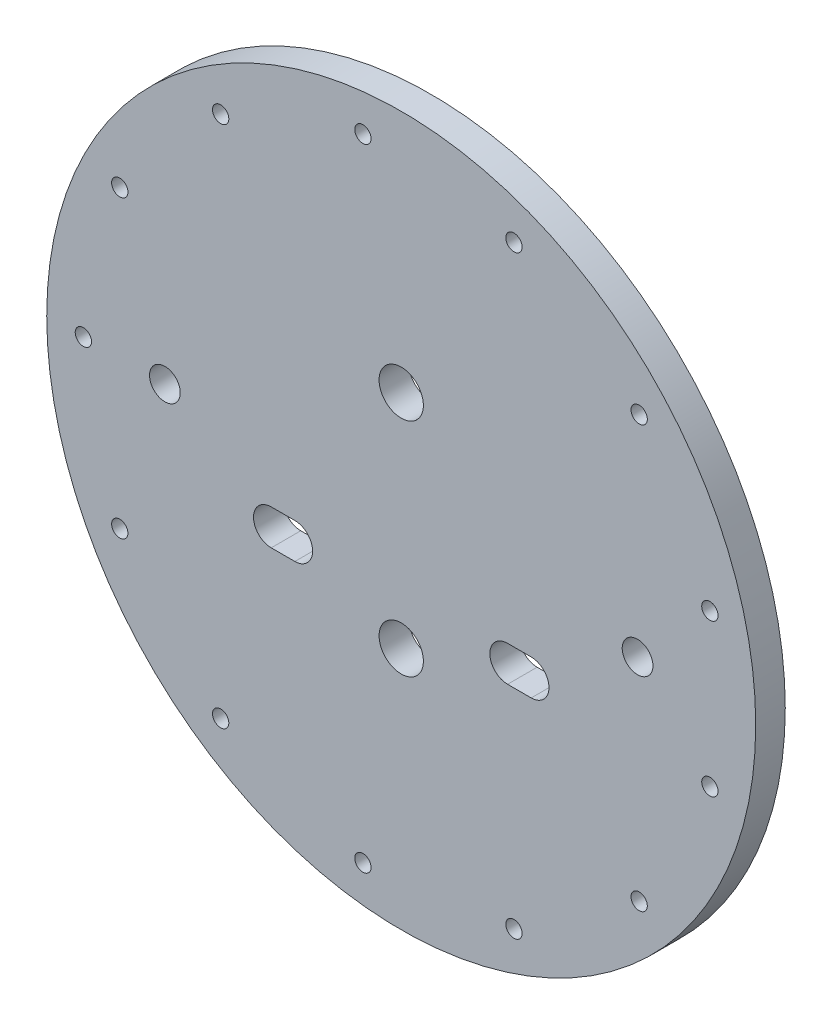
SolidWorks part; units mm, degrees
material "Balsa"
ref_plane "Front" through (0, 0, 0) normal (0, 0, 1) x (1, 0, 0)
ref_plane "Top" through (0, 0, 0) normal (0, 1, 0) x (1, 0, 0)
ref_plane "Right" through (0, 0, 0) normal (1, 0, 0) x (0, 0, -1)
sketch "Sketch2" plane through (0, 0, 0) normal (0, 0, 1) x (1, 0, 0)
  line L0 (-56.2467, 0) -> (91.426, 0) construction
  line L1 (0, 58.7371) -> (0, -82.5124) construction
  circle A0 centre (0, 0) radius 76.2
  circle A1 centre (-50.8, 0) radius 3.302
  circle A2 centre (50.8, 0) radius 3.302
  circle A3 centre (0, 23.8125) radius 4.7625
  circle A4 centre (0, -23.8125) radius 4.7625
  dimension "D1" = 152.4
  dimension "D2" = 47.625
  dimension "D4" = 9.525
  dimension "D5" = 101.6
  dimension "D6" = 6.604
  dimension "D3" = 23.8125
  dimension "D7" = 50.8
extrude "Boss-Extrude1" add sketch "Sketch2" along normal mid plane 6.35
sketch "Sketch3" plane through (0, 0, -3.175) normal (0, 0, -1) x (-1, 0, 0)
  line L0 (-27.94, -15.24) -> (-22.86, -15.24) construction
  line L1 (-27.94, -11.43) -> (-22.86, -11.43)
  line L2 (-27.94, -19.05) -> (-22.86, -19.05)
  arc A2 (-27.94, -11.43) -> (-27.94, -19.05) centre (-27.94, -15.24) ccw
  arc A11 (-22.86, -19.05) -> (-22.86, -11.43) centre (-22.86, -15.24) ccw
  point P4 (-25.4, -15.24)
  dimension "D3" = 5.08
  dimension "D4" = 15.24
  dimension "D5" = 22.86
  dimension "0.05" = 3.81
extrude "Cut-Extrude1" cut sketch "Sketch3" against normal blind 6.35
mirror "Mirror1" about plane through (0, 0, 0) normal (1, 0, 0) of "Cut-Extrude1"
sketch "Sketch4" plane through (0, 0, 3.175) normal (0, 0, 1) x (1, 0, 0)
  circle A0 centre (-68.326, 0) radius 1.7526
  dimension "D1" = 3.5052
  dimension "D2" = 68.326
extrude "Cut-Extrude2" cut sketch "Sketch4" against normal blind 18.034
pattern_circular "CirPattern1" count 13 over 360 about axis through (0, 0, 0) along (0, 0, 1) of "Cut-Extrude2"
